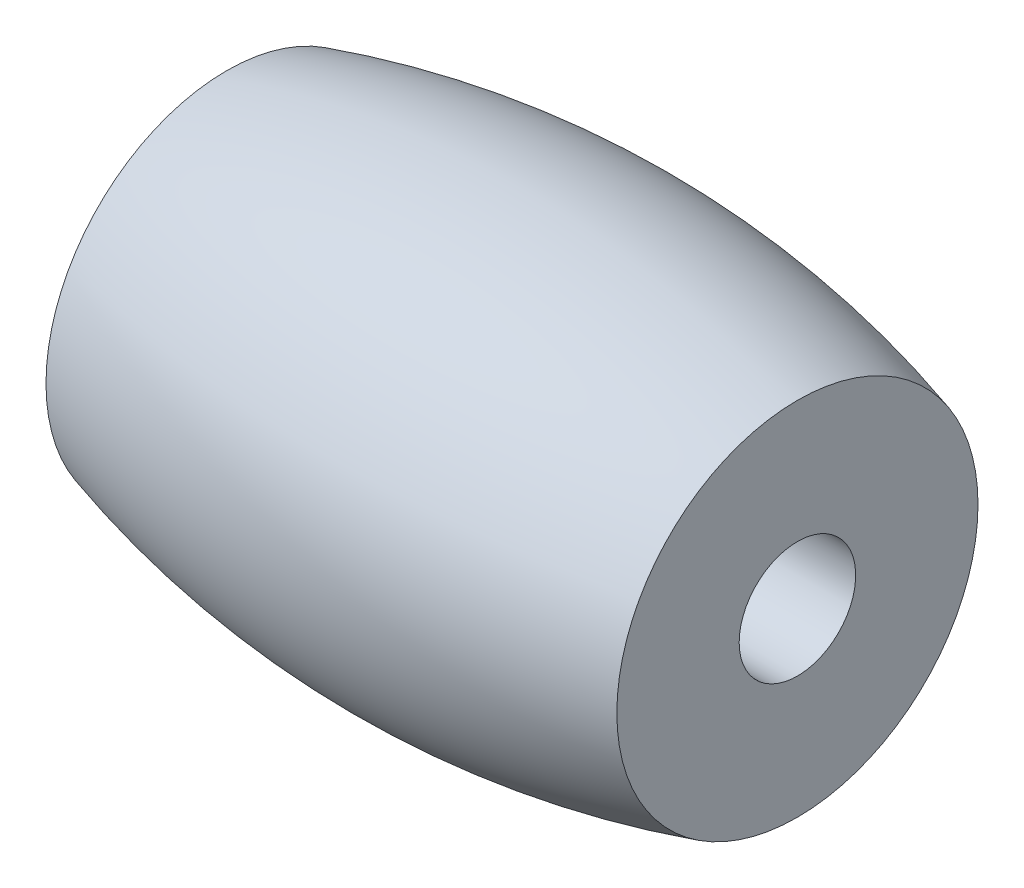
SolidWorks part; units mm, degrees
ref_plane "Alzado" through (0, 0, 0) normal (0, 0, 1) x (1, 0, 0)
ref_plane "Planta" through (0, 0, 0) normal (0, 1, 0) x (1, 0, 0)
ref_plane "Vista lateral" through (0, 0, 0) normal (1, 0, 0) x (0, 0, -1)
sketch "Croquis1" plane through (0, 0, 0) normal (0, 1, 0) x (1, 0, 0)
  line L1 (-12.25, -9.5) -> (12.25, -9.5)
  line L2 (-12.25, -9.5) -> (-12.25, 9.5)
  line L3 (-12.25, 9.5) -> (12.25, 9.5)
  line L4 (12.25, -9.5) -> (12.25, 9.5)
  line L5 (-12.25, -9.5) -> (12.25, 9.5) construction
  line L6 (-12.25, 9.5) -> (12.25, -9.5) construction
  point P0 (0, 0)
  dimension "D1" = 24.5
  dimension "D2" = 19
extrude "Saliente-Extruir1" add sketch "Croquis1" along normal blind 19
ref_plane "Plano1" through (0, 9.5, 0) normal (0, 1, 0) x (1, 0, 0)
ref_axis "Eje1" through (-13.475, 9.5, 0) along (1, 0, 0)
sketch "Croquis2" plane through (0, 9.5, 0) normal (0, 1, 0) x (1, 0, 0)
  line L1 (-12.25, 9.5) -> (-12.25, -9.5) construction
  line L4 (12.25, -9.5) -> (12.25, 9.5) construction
  line L9 (-12.25, 7.75) -> (-12.25, 18.2215)
  line L10 (-12.25, 18.2215) -> (12.25, 18.2215)
  line L11 (12.25, 18.2215) -> (12.25, 7.75)
  arc A0 (-12.25, 7.75) -> (12.25, 7.75) centre (0, -34.25) cw
revolve "Cortar-Revolución2" cut sketch "Croquis2" angle 360 about axis through (-13.475, 9.5, 0) along (1, 0, 0)
sketch "Croquis4" plane through (-12.25, 0, 0) normal (-1, 0, 0) x (0, 0, 1)
  circle A0 centre (0, 9.5) radius 2.5
  dimension "D1" = 5
extrude "Cortar-Extruir1" cut sketch "Croquis4" against normal blind 34.5
